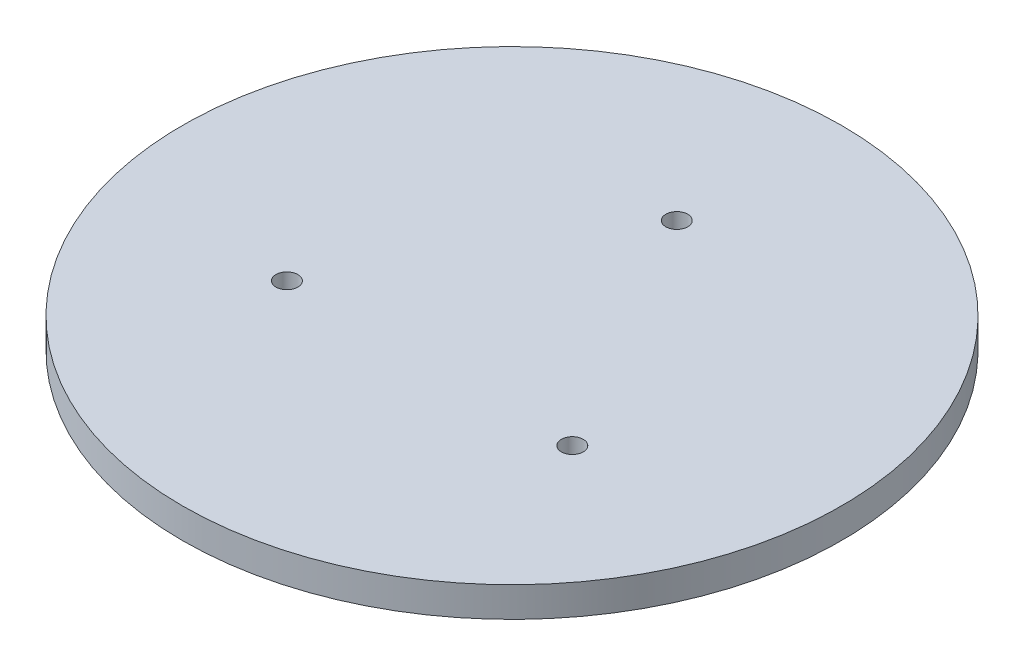
SolidWorks part; units mm, degrees
ref_plane "Front Plane" through (0, 0, 0) normal (0, 0, 1) x (1, 0, 0)
ref_plane "Top Plane" through (0, 0, 0) normal (0, 1, 0) x (1, 0, 0)
ref_plane "Right Plane" through (0, 0, 0) normal (1, 0, 0) x (0, 0, -1)
sketch "Sketch1" plane through (0, 0, 0) normal (0, 1, 0) x (1, 0, 0)
  line L0 (0, 0) -> (0, 69.596) construction
  circle A0 centre (0, 0) radius 69.596
  circle A1 centre (0, 34.798) radius 2.3114
  circle A2 centre (30.136, -17.399) radius 2.3114
  circle A3 centre (-30.136, -17.399) radius 2.3114
  point P13 (0, 0)
  dimension "D1" = 139.192
  dimension "D2" = 4.6228
  dimension "D3" = 3
extrude "Boss-Extrude1" add sketch "Sketch1" along normal blind 6.35
